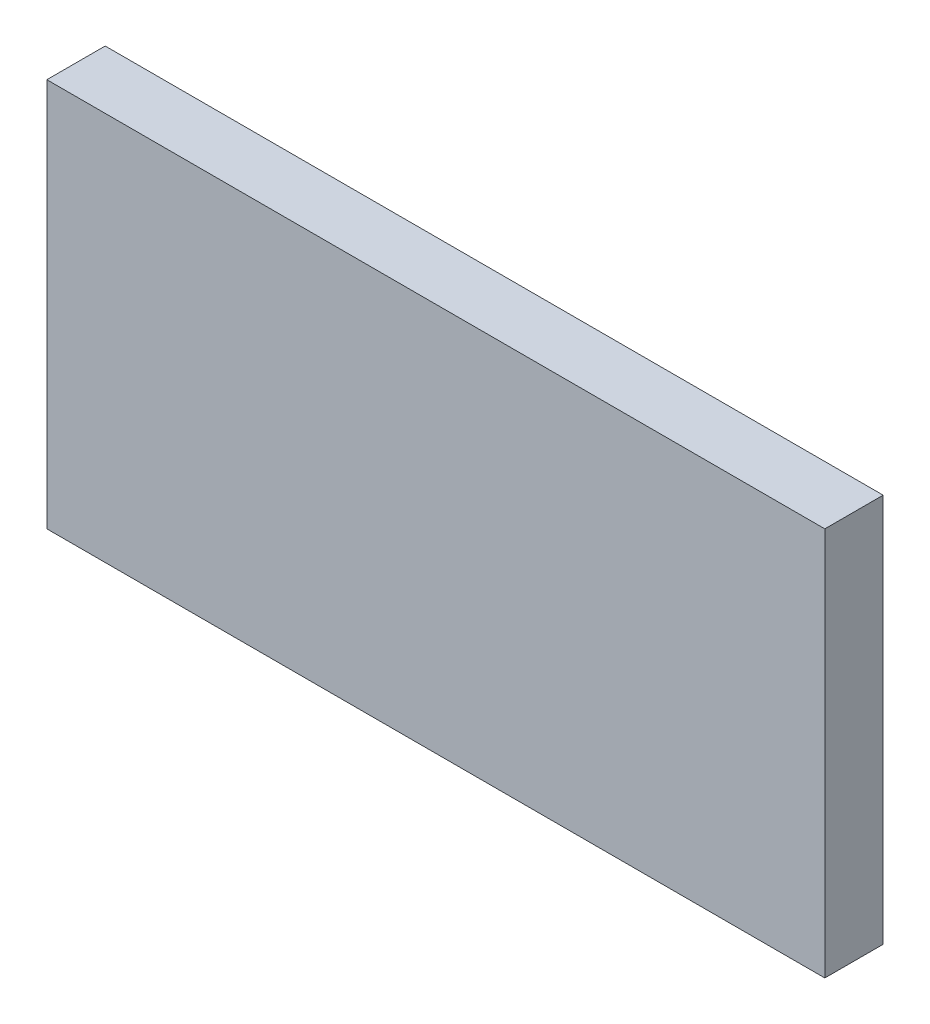
SolidWorks part; units mm, degrees
ref_plane "Front" through (0, 0, 0) normal (0, 0, 1) x (1, 0, 0)
ref_plane "Top" through (0, 0, 0) normal (0, 1, 0) x (1, 0, 0)
ref_plane "Right" through (0, 0, 0) normal (1, 0, 0) x (0, 0, -1)
sketch "Sketch1" plane through (0, 0, 0) normal (0, 0, 1) x (1, 0, 0)
  line L1 (-19.0244, 8.7952) -> (20.9756, 8.7952)
  line L2 (-19.0244, 8.7952) -> (-19.0244, -11.2048)
  line L3 (-19.0244, -11.2048) -> (20.9756, -11.2048)
  line L4 (20.9756, 8.7952) -> (20.9756, -11.2048)
  dimension "D1" = 40
  dimension "D2" = 20
extrude "Boss-Extrude1" add sketch "Sketch1" along normal blind 3
